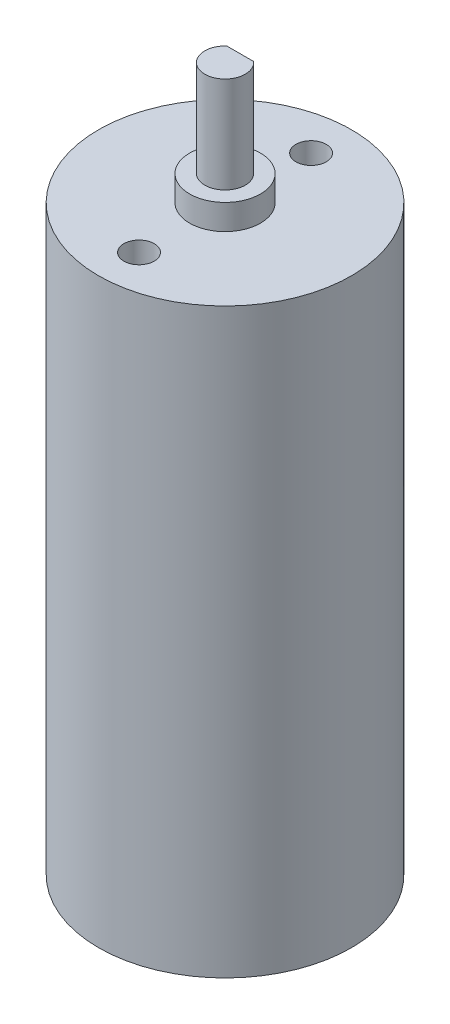
SolidWorks part; units mm, degrees
ref_plane "前视基准面" through (0, 0, 0) normal (0, 0, 1) x (1, 0, 0)
ref_plane "上视基准面" through (0, 0, 0) normal (0, 1, 0) x (1, 0, 0)
ref_plane "右视基准面" through (0, 0, 0) normal (1, 0, 0) x (0, 0, -1)
sketch "草图1" plane through (0, 0, 0) normal (0, 1, 0) x (1, 0, 0)
  circle A0 centre (0, 0) radius 12.5
  dimension "D1" = 25
extrude "凸台-拉伸1" add sketch "草图1" along normal blind 57.5
sketch "草图2" plane through (0, 57.5, 0) normal (0, 1, 0) x (1, 0, 0)
  circle A0 centre (0, 0) radius 3.5
  dimension "D1" = 7
extrude "凸台-拉伸2" add sketch "草图2" along normal blind 2.5
sketch "草图3" plane through (0, 60, 0) normal (0, 1, 0) x (1, 0, 0)
  circle A0 centre (0, 0) radius 2
  dimension "D1" = 4
extrude "凸台-拉伸3" add sketch "草图3" along normal blind 9.5
sketch "草图4" plane through (0, 69.5, 0) normal (0, 1, 0) x (1, 0, 0)
  line L0 (-1.3229, 1.5) -> (1.3229, 1.5)
  line L1 (0, 1.5) -> (0, -2) construction
  circle A0 centre (0, 0) radius 2 construction
  circle A1 centre (0, 0) radius 2 construction
  circle A2 centre (0, 0) radius 2
  point P7 (0, -2)
  circle M3 centre (0, 0) radius 2
  dimension "D1" = 3.5
extrude "切除-拉伸1" cut sketch "草图4" against normal blind 8 contours L0 M3
sketch "草图5" plane through (0, 57.5, 0) normal (0, 1, 0) x (1, 0, 0)
  circle A0 centre (0, 0) radius 8.5 construction
  circle A1 centre (0, 8.5) radius 1.5
  circle A2 centre (0, -8.5) radius 1.5
  dimension "D1" = 17
  dimension "D2" = 3
extrude "切除-拉伸2" cut sketch "草图5" against normal blind 5
